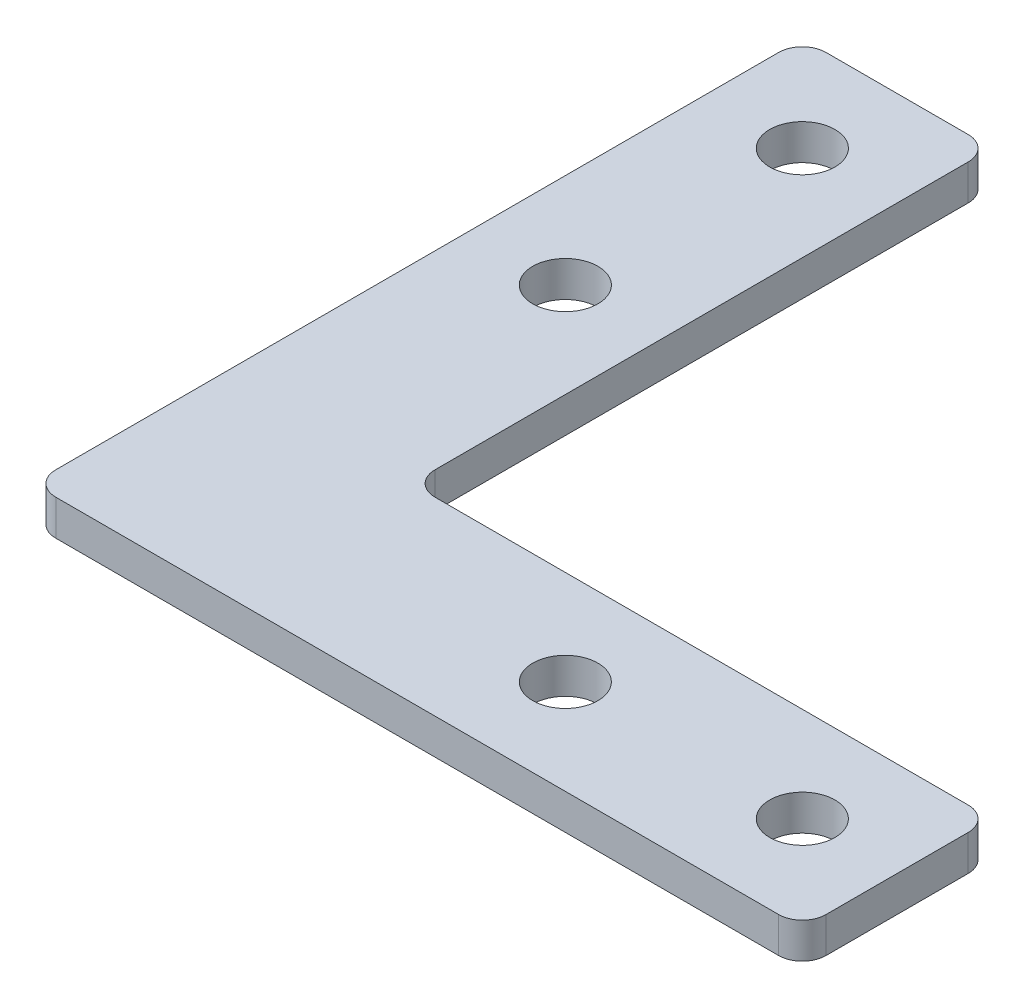
SolidWorks part; units mm, degrees
ref_plane "前视基准面" through (0, 0, 0) normal (0, 0, 1) x (1, 0, 0)
ref_plane "上视基准面" through (0, 0, 0) normal (0, 1, 0) x (1, 0, 0)
ref_plane "右视基准面" through (0, 0, 0) normal (1, 0, 0) x (0, 0, -1)
other "Configuration Table"
sketch "草图1" plane through (0, 0, 0) normal (0, 1, 0) x (1, 0, 0)
  line L0 (-36.3186, 40.422) -> (-36.3186, -20.578)
  line L1 (-34.3186, -22.578) -> (26.6814, -22.578)
  line L2 (28.6814, -20.578) -> (28.6814, -8.578)
  line L3 (26.6814, -6.578) -> (-18.3186, -6.578)
  line L4 (-20.3186, -4.578) -> (-20.3186, 40.422)
  line L5 (-22.3186, 42.422) -> (-34.3186, 42.422)
  line L6 (-20.3186, -6.578) -> (-35375.6577, -35361.917) construction
  line L7 (28.6814, -14.578) -> (-49971.3186, -14.578) construction
  circle A0 centre (20.6814, -14.578) radius 2.75
  circle A1 centre (0.6814, -14.578) radius 2.75
  circle A2 centre (-28.3186, 34.422) radius 2.75
  circle A3 centre (-28.3186, 14.422) radius 2.75
  arc A4 (-36.3186, -20.578) -> (-34.3186, -22.578) centre (-34.3186, -20.578) ccw
  arc A5 (26.6814, -22.578) -> (28.6814, -20.578) centre (26.6814, -20.578) ccw
  arc A6 (28.6814, -8.578) -> (26.6814, -6.578) centre (26.6814, -8.578) ccw
  arc A7 (-18.3186, -6.578) -> (-20.3186, -4.578) centre (-18.3186, -4.578) cw
  arc A8 (-20.3186, 40.422) -> (-22.3186, 42.422) centre (-22.3186, 40.422) ccw
  arc A9 (-36.3186, 40.422) -> (-34.3186, 42.422) centre (-34.3186, 40.422) cw
  point P9 (28.6814, -14.578)
  point P20 (-36.3186, -22.578)
  point P23 (28.6814, -22.578)
  point P27 (28.6814, -6.578)
  point P30 (-20.3186, -6.578)
  point P33 (-20.3186, 42.422)
  point P36 (-36.3186, 42.422)
  dimension "D5" = 5.5
  dimension "D6" = 5.5
  dimension "D9" = 2
  dimension "D1" = 65
  dimension "D2" = 65
  dimension "D3" = 16
  dimension "D4" = 16
  dimension "D7" = 20
  dimension "D8" = 8
extrude "凸台-拉伸1" add sketch "草图1" along normal blind 3
